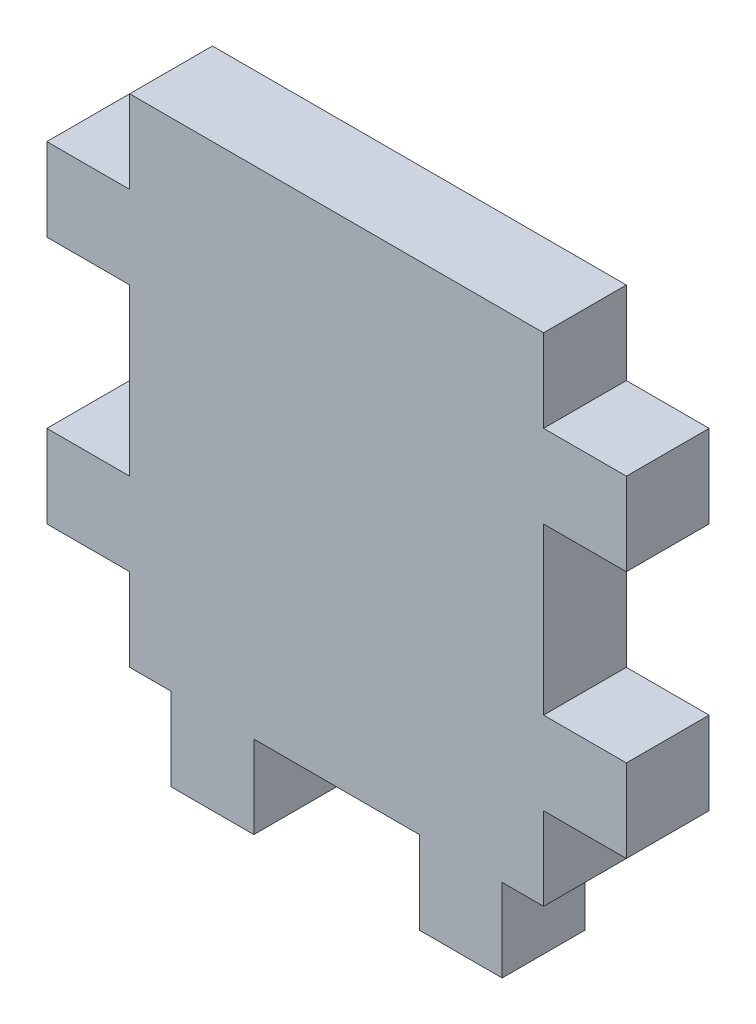
SolidWorks part; units mm, degrees
ref_plane "Front Plane" through (0, 0, 0) normal (0, 0, 1) x (1, 0, 0)
ref_plane "Top Plane" through (0, 0, 0) normal (0, 1, 0) x (1, 0, 0)
ref_plane "Right Plane" through (0, 0, 0) normal (1, 0, 0) x (0, 0, -1)
sketch "Sketch1" plane through (0, 0, 0) normal (0, 0, 1) x (1, 0, 0)
  line L0 (0, 0) -> (0, 5)
  line L1 (0, 5) -> (-2.5, 5)
  line L2 (-2.5, 5) -> (-2.5, 10.0003)
  line L3 (-2.5, 10.0003) -> (-7.5, 10.0003)
  line L4 (-7.5, 10.0003) -> (-7.5, 15.0003)
  line L5 (-7.5, 15.0003) -> (-2.5, 15.0003)
  line L6 (-2.5, 15.0003) -> (-2.5, 25.0003)
  line L7 (-2.5, 25.0003) -> (-7.5, 25.0003)
  line L8 (-7.5, 25.0003) -> (-7.5, 30.0003)
  line L9 (-7.5, 30.0003) -> (-2.5, 30.0003)
  line L10 (-2.5, 30.0003) -> (-2.5, 35)
  line L11 (-2.5, 35) -> (22.5, 35)
  line L12 (22.5, 35) -> (22.5, 30.0003)
  line L13 (22.5, 30.0003) -> (27.5, 30.0003)
  line L14 (27.5, 30.0003) -> (27.5, 25.0003)
  line L15 (27.5, 25.0003) -> (22.5, 25.0003)
  line L16 (22.5, 25.0003) -> (22.5, 15.0003)
  line L17 (22.5, 15.0003) -> (27.5, 15.0003)
  line L18 (27.5, 15.0003) -> (27.5, 10.0003)
  line L19 (27.5, 10.0003) -> (22.5, 10.0003)
  line L20 (22.5, 10.0003) -> (22.5, 5)
  line L21 (22.5, 5) -> (20, 5)
  line L22 (20, 5) -> (20, 0)
  line L23 (20, 0) -> (15, 0)
  line L24 (15, 0) -> (15, 5)
  line L25 (15, 5) -> (5, 5)
  line L26 (5, 5) -> (5, 0)
  line L27 (5, 0) -> (0, 0)
  line L28 (10, 38.8616) -> (10, -3.1032) construction
  point P31 (10, 35)
  dimension "D1" = 5
  dimension "D2" = 10
  dimension "D3" = 5
  dimension "D4" = 10
  dimension "D5" = 25
  dimension "D6" = 30
extrude "Boss-Extrude1" add sketch "Sketch1" along normal blind 5
